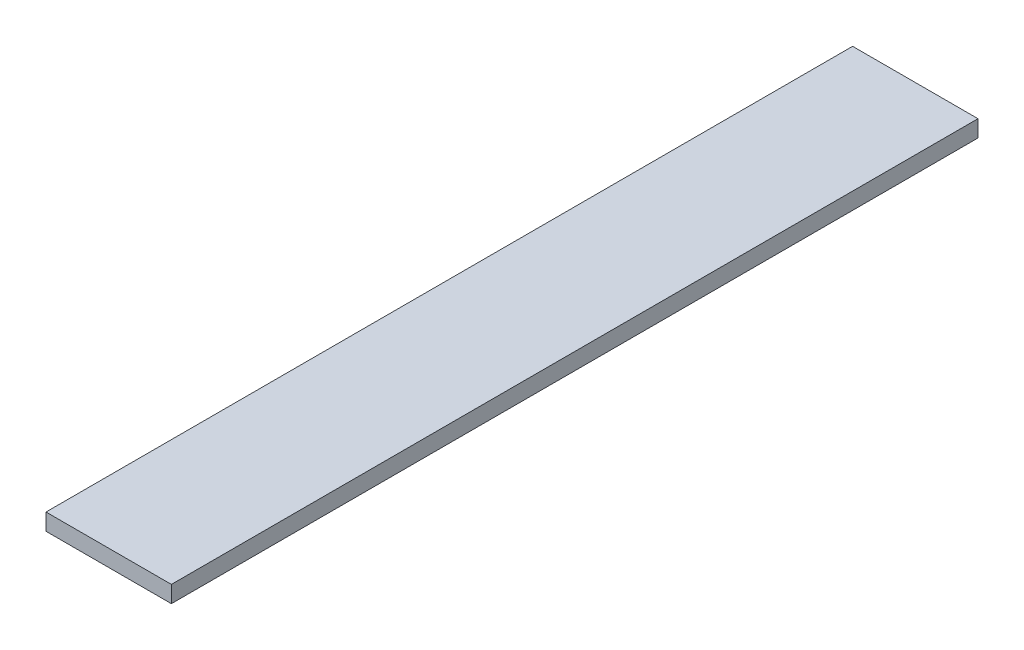
SolidWorks part; units mm, degrees
ref_plane "Alzado" through (0, 0, 0) normal (0, 0, 1) x (1, 0, 0)
ref_plane "Planta" through (0, 0, 0) normal (0, 1, 0) x (1, 0, 0)
ref_plane "Vista lateral" through (0, 0, 0) normal (1, 0, 0) x (0, 0, -1)
sketch "Croquis1" plane through (0, 0, 0) normal (0, 0, 1) x (1, 0, 0)
  line L0 (-96.226, 0) -> (-96.226, 40)
  line L1 (-96.226, 40) -> (203.774, 40)
  line L2 (-96.226, 0) -> (203.774, 0)
  line L3 (203.774, 0) -> (203.774, 40)
  dimension "D1" = 40
  dimension "D2" = 300
extrude "Saliente-Extruir1" add sketch "Croquis1" along normal blind 1930
